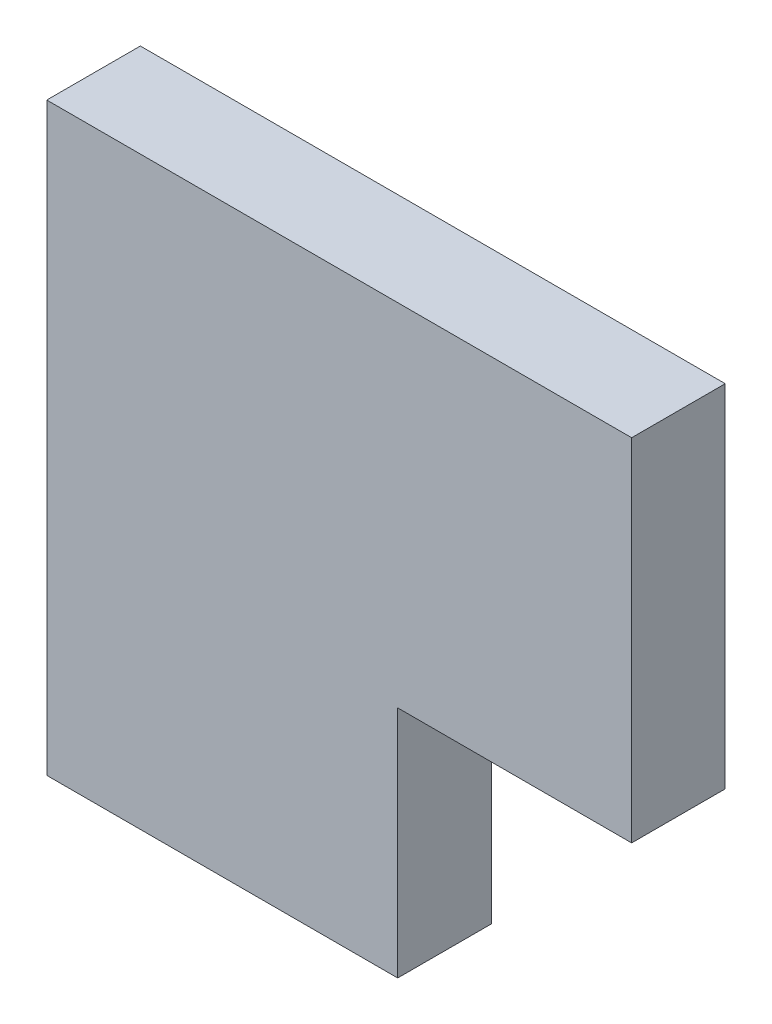
SolidWorks part; units mm, degrees
material "PBT General Purpose"
ref_plane "Front Plane" through (0, 0, 0) normal (0, 0, 1) x (1, 0, 0)
ref_plane "Top Plane" through (0, 0, 0) normal (0, 1, 0) x (1, 0, 0)
ref_plane "Right Plane" through (0, 0, 0) normal (1, 0, 0) x (0, 0, -1)
sketch "Sketch1" plane through (0, 0, 0) normal (0, 0, 1) x (1, 0, 0)
  line L0 (0, 0) -> (0, 1.5)
  line L1 (0, 1.5) -> (-2.5, 1.5)
  line L2 (-2.5, 1.5) -> (-2.5, -1)
  line L3 (-2.5, -1) -> (-1, -1)
  line L4 (-1, -1) -> (-1, 0)
  line L5 (-1, 0) -> (0, 0)
  dimension "D1" = 1.5
  dimension "D2" = 1
  dimension "D3" = 1
  dimension "D4" = 1.5
extrude "Boss-Extrude1" add sketch "Sketch1" along normal mid plane 0.4
equation "\"t\"= 0.4'thickness of the sheets"
equation "\"FlexJoint\"= 0.25'Width of flextures"
equation "\"FoldJoint\"= 0.5'Width of folding joints"
equation "\"AssembleAngle\"= 0'Angle of assembly parts"
equation "\"D1@Boss-Extrude1\"=\"t\""
